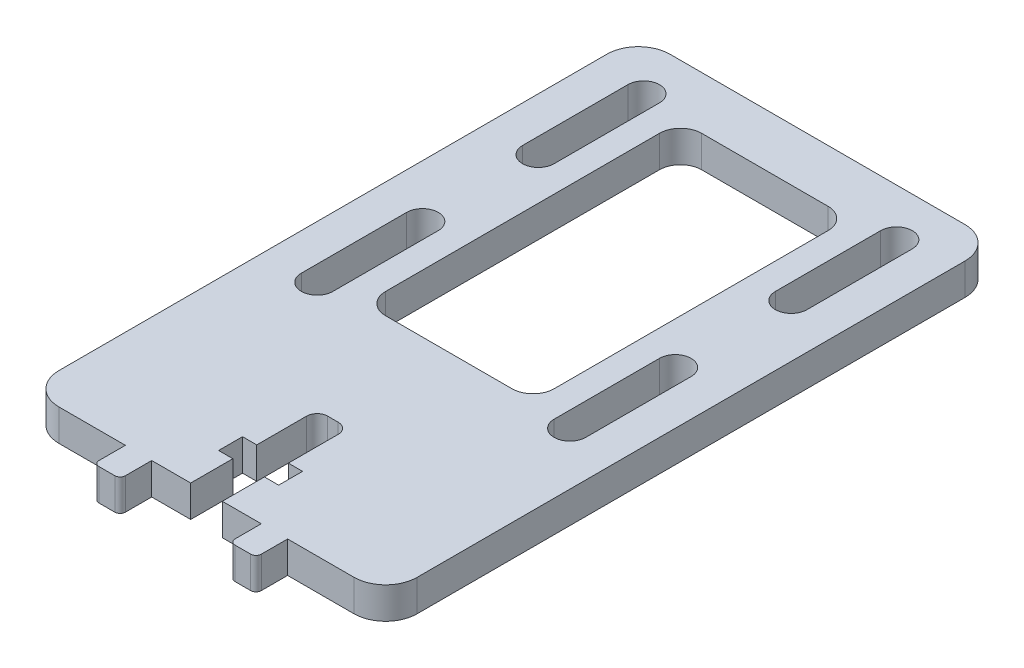
SolidWorks part; units mm, degrees
ref_plane "Plano frontal" through (0, 0, 0) normal (0, 0, 1) x (1, 0, 0)
ref_plane "Plano superior" through (0, 0, 0) normal (0, 1, 0) x (1, 0, 0)
ref_plane "Plano direito" through (0, 0, 0) normal (1, 0, 0) x (0, 0, -1)
sketch "Sketch1" plane through (0, 0, 0) normal (0, 1, 0) x (1, 0, 0)
  line L1 (17, -29) -> (-17, -29)
  line L2 (17, -29) -> (17, 29)
  line L3 (17, 29) -> (-17, 29)
  line L4 (-17, -29) -> (-17, 29)
  line L5 (17, -29) -> (-17, 29) construction
  line L6 (17, 29) -> (-17, -29) construction
  point P0 (0, 0)
  dimension "D1" = 34
  dimension "D2" = 58
extrude "Boss-Extrude1" add sketch "Sketch1" along normal mid plane 3
sketch "Sketch3" plane through (0, 0, 0) normal (0, 1, 0) x (1, 0, 0)
  line L0 (17, 29) -> (-17, 29) construction
  line L1 (-12, -6) -> (-12, 24) construction
  line L2 (-12, -6) -> (12, -6) construction
  line L3 (12, -6) -> (12, 24) construction
  line L4 (-12, 24) -> (12, 24) construction
  line L5 (-12, -6.5) -> (-12, 3.5) construction
  line L6 (-12, 14.5) -> (-12, 24.5) construction
  line L13 (-13.5, 14.5) -> (-13.5, 24.5)
  line L14 (-10.5, 14.5) -> (-10.5, 24.5)
  line L17 (-13.5, -6.5) -> (-13.5, 3.5)
  line L18 (-10.5, -6.5) -> (-10.5, 3.5)
  line L19 (-17, 29) -> (-17, -29) construction
  line L20 (0, -1.65) -> (0, 1.65) construction
  line L21 (12, -6.5) -> (12, 3.5) construction
  line L22 (13.5, -6.5) -> (13.5, 3.5)
  line L23 (10.5, -6.5) -> (10.5, 3.5)
  line L24 (12, 14.5) -> (12, 24.5) construction
  line L25 (13.5, 14.5) -> (13.5, 24.5)
  line L26 (10.5, 14.5) -> (10.5, 24.5)
  line L28 (-6, 24) -> (6, 24)
  line L29 (-8, 22) -> (-8, -4)
  line L30 (-6, -6) -> (6, -6)
  line L31 (8, 22) -> (8, -4)
  circle A4 centre (12, -1.5) radius 1.5 construction
  circle A7 centre (-12, -1.5) radius 1.5 construction
  circle A8 centre (-12, 19.5) radius 1.5 construction
  circle A10 centre (12, 19.5) radius 1.5 construction
  arc A11 (-13.5, 14.5) -> (-10.5, 14.5) centre (-12, 14.5) ccw
  arc A12 (-10.5, 24.5) -> (-13.5, 24.5) centre (-12, 24.5) ccw
  arc A13 (-13.5, -6.5) -> (-10.5, -6.5) centre (-12, -6.5) ccw
  arc A14 (-10.5, 3.5) -> (-13.5, 3.5) centre (-12, 3.5) ccw
  arc A15 (13.5, -6.5) -> (10.5, -6.5) centre (12, -6.5) cw
  arc A16 (10.5, 3.5) -> (13.5, 3.5) centre (12, 3.5) cw
  arc A17 (13.5, 14.5) -> (10.5, 14.5) centre (12, 14.5) cw
  arc A18 (10.5, 24.5) -> (13.5, 24.5) centre (12, 24.5) cw
  arc A19 (6, -6) -> (8, -4) centre (6, -4) ccw
  arc A20 (-8, -4) -> (-6, -6) centre (-6, -4) ccw
  arc A21 (6, 24) -> (8, 22) centre (6, 22) cw
  arc A22 (-6, 24) -> (-8, 22) centre (-6, 22) ccw
  point P14 (-12, 19.5)
  point P19 (0, 24)
  point P23 (-12, -1.5)
  point P31 (0, 24)
  point P36 (12, -1.5)
  point P43 (12, 19.5)
  point P54 (8, -6)
  point P61 (-8, 24)
  dimension "D4" = 10
  dimension "D5" = 3
  dimension "D6" = 3
  dimension "D7" = 2.5
  dimension "D8" = 2
  dimension "D2" = 3
  dimension "D3" = 3
  dimension "D1" = 24
  dimension "D12" = 30
extrude "Cut-Extrude1" cut sketch "Sketch3" against normal through all both and the other way through all
sketch "Sketch5" plane through (0, 0, 0) normal (0, 1, 0) x (1, 0, 0)
  line L0 (-17, -29) -> (17, -29) construction
  line L1 (-1.5, -29) -> (1.5, -29)
  line L2 (-1.5, -29) -> (-1.5, -25)
  line L3 (-0.5, -17) -> (0.5, -17)
  line L4 (1.5, -29) -> (1.5, -25)
  line L6 (1.5, -22.73) -> (2.85, -22.73)
  line L7 (-2.85, -22.73) -> (-1.5, -22.73)
  line L8 (-2.85, -22.73) -> (-2.85, -25)
  line L9 (-2.85, -25) -> (-1.5, -25)
  line L10 (2.85, -22.73) -> (2.85, -25)
  line L11 (-1.5, -22.73) -> (-1.5, -18)
  line L12 (1.5, -25) -> (2.85, -25)
  line L13 (1.5, -22.73) -> (1.5, -18)
  arc A0 (0.5, -17) -> (1.5, -18) centre (0.5, -18) cw
  arc A1 (-1.5, -18) -> (-0.5, -17) centre (-0.5, -18) cw
  point P6 (0, -17)
  point P20 (1.5, -17)
  point P23 (-1.5, -17)
  dimension "D8" = 1
  dimension "D1" = 3
  dimension "D2" = 12
  dimension "D3" = 4
  dimension "D4" = 2.27
  dimension "D5" = 1.35
  dimension "D6" = 1.35
extrude "Cut-Extrude2" cut sketch "Sketch5" against normal through all both and the other way through all
sketch "Sketch8" plane through (0, 0, 0) normal (0, 1, 0) x (1, 0, 0)
  line L0 (-17, -29) -> (-1.5, -29) construction
  line L1 (-7.7, -29) -> (-5.2, -29)
  line L2 (-7.7, -29) -> (-7.7, -31.5)
  line L3 (-7.2, -32) -> (-5.7, -32)
  line L4 (-5.2, -29) -> (-5.2, -31.5)
  line L5 (-1.5, -25) -> (-1.5, -29) construction
  line L6 (0, -1.65) -> (0, 1.65) construction
  line L7 (5.2, -29) -> (5.2, -31.5)
  line L8 (7.2, -32) -> (5.7, -32)
  line L9 (7.7, -29) -> (7.7, -31.5)
  line L10 (7.7, -29) -> (5.2, -29)
  arc A0 (7.2, -32) -> (7.7, -31.5) centre (7.2, -31.5) ccw
  arc A1 (5.2, -31.5) -> (5.7, -32) centre (5.7, -31.5) ccw
  arc A2 (-5.7, -32) -> (-5.2, -31.5) centre (-5.7, -31.5) ccw
  arc A3 (-7.7, -31.5) -> (-7.2, -32) centre (-7.2, -31.5) ccw
  point P16 (7.7, -32)
  point P19 (5.2, -32)
  point P22 (-5.2, -32)
  point P25 (-7.7, -32)
  dimension "D4" = 0.5
  dimension "D1" = 2.5
  dimension "D2" = 3.7
  dimension "D3" = 3
extrude "Boss-Extrude3" add sketch "Sketch8" along normal mid plane 3
fillet "Fillet1" radius 3 4 edges at (17, 0, -29) (-17, 0, -29) (17, 0, 29) (-17, 0, 29)
sketch "Sketch7" plane through (0, 0, 29) normal (0, 0, 1) x (1, 0, 0)
  circle A0 centre (0, 0) radius 1.5 construction
  dimension "D1" = 3
